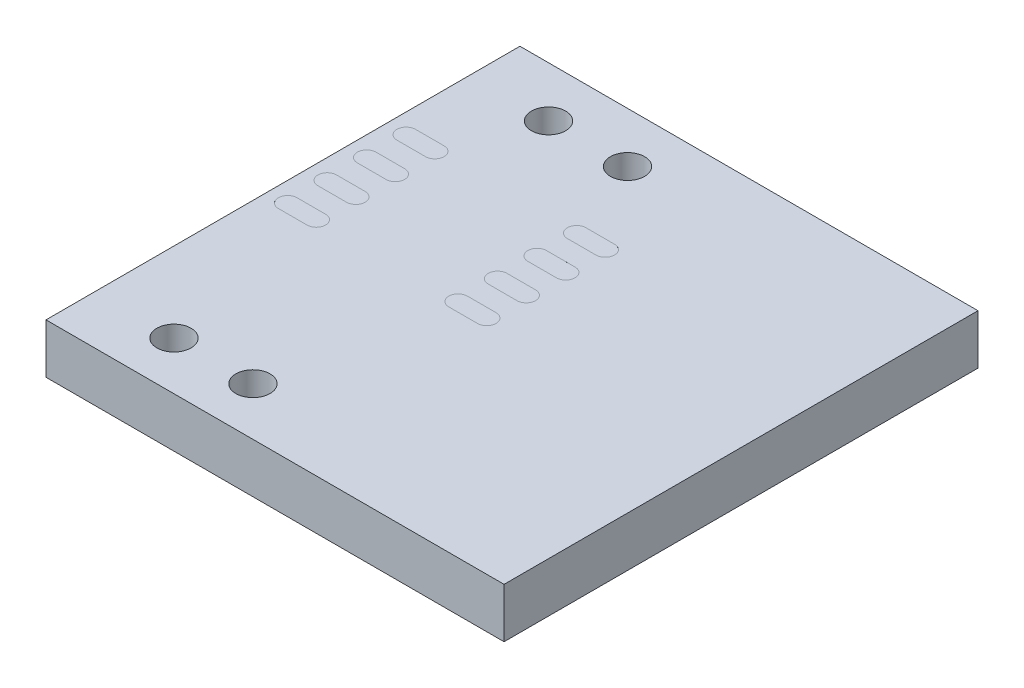
SolidWorks part; units mm, degrees
ref_plane "Front" through (0, 0, 0) normal (0, 0, 1) x (1, 0, 0)
ref_plane "Top" through (0, 0, 0) normal (0, 1, 0) x (1, 0, 0)
ref_plane "Right" through (0, 0, 0) normal (1, 0, 0) x (0, 0, -1)
sketch "Эскиз1" plane through (0, 0, 0) normal (0, 1, 0) x (1, 0, 0)
  line L1 (-7.365, 7.62) -> (7.365, 7.62)
  line L2 (-7.365, 7.62) -> (-7.365, -7.62)
  line L3 (-7.365, -7.62) -> (7.365, -7.62)
  line L4 (7.365, 7.62) -> (7.365, -7.62)
  line L5 (-7.365, 7.62) -> (7.365, -7.62) construction
  line L6 (-7.365, -7.62) -> (7.365, 7.62) construction
  point P0 (0, 0)
  dimension "D1" = 14.73
  dimension "D2" = 15.24
extrude "Бобышка-Вытянуть1" add sketch "Эскиз1" along normal blind 1.6
sketch "Эскиз2" plane through (0, 1.6, 0) normal (0, 1, 0) x (1, 0, 0)
  line L0 (-7.365, 7.62) -> (-7.365, -7.62) construction
  line L1 (7.365, 7.62) -> (-7.365, 7.62) construction
  line L2 (-7.365, -7.62) -> (7.365, -7.62) construction
  circle A0 centre (-4.825, 6) radius 0.55
  circle A1 centre (-2.285, 6) radius 0.55
  circle A2 centre (-4.8, -6.07) radius 0.55
  circle A3 centre (-2.26, -6.071) radius 0.55
  dimension "D5" = 1.1
  dimension "D6" = 1.1
  dimension "D11" = 1.1
  dimension "D12" = 1.1
  dimension "D1" = 2.54
  dimension "D2" = 2.54
  dimension "D3" = 1.62
  dimension "D4" = 1.62
  dimension "D7" = 2.565
  dimension "D8" = 2.54
  dimension "D9" = 1.549
  dimension "D10" = 1.55
extrude "Вырез-Вытянуть1" cut sketch "Эскиз2" against normal through all
sketch "Эскиз3" plane through (0, 1.6, 0) normal (0, 1, 0) x (1, 0, 0)
  line L0 (-6.729, 3.327) -> (-5.809, 3.327) construction
  line L1 (-6.729, 3.627) -> (-5.809, 3.627)
  line L2 (-6.729, 3.027) -> (-5.809, 3.027)
  line L3 (-7.365, 7.62) -> (-7.365, -7.62) construction
  line L4 (7.365, 7.62) -> (-7.365, 7.62) construction
  line L5 (-6.729, 2.057) -> (-5.809, 2.057) construction
  line L6 (-6.729, 2.357) -> (-5.809, 2.357)
  line L7 (-6.729, 1.757) -> (-5.809, 1.757)
  line L8 (-6.729, 0.787) -> (-5.809, 0.787) construction
  line L9 (-6.729, 1.087) -> (-5.809, 1.087)
  line L10 (-6.729, 0.487) -> (-5.809, 0.487)
  line L11 (-6.729, -0.483) -> (-5.809, -0.483) construction
  line L12 (-6.729, -0.183) -> (-5.809, -0.183)
  line L13 (-6.729, -0.783) -> (-5.809, -0.783)
  line L14 (-1.249, 2.057) -> (-0.329, 2.057) construction
  line L15 (-1.249, 2.357) -> (-0.329, 2.357)
  line L16 (-1.249, 1.757) -> (-0.329, 1.757)
  line L17 (-1.249, 0.787) -> (-0.329, 0.787) construction
  line L18 (-1.249, 1.087) -> (-0.329, 1.087)
  line L19 (-1.249, 0.487) -> (-0.329, 0.487)
  line L20 (-1.249, -0.483) -> (-0.329, -0.483) construction
  line L21 (-1.249, -0.183) -> (-0.329, -0.183)
  line L22 (-1.249, -0.783) -> (-0.329, -0.783)
  line L23 (-1.249, 3.327) -> (-0.329, 3.327) construction
  line L24 (-1.249, 3.627) -> (-0.329, 3.627)
  line L25 (-1.249, 3.027) -> (-0.329, 3.027)
  arc A0 (-6.729, 3.627) -> (-6.729, 3.027) centre (-6.729, 3.327) ccw
  arc A1 (-5.809, 3.027) -> (-5.809, 3.627) centre (-5.809, 3.327) ccw
  arc A2 (-6.729, 2.357) -> (-6.729, 1.757) centre (-6.729, 2.057) ccw
  arc A3 (-5.809, 1.757) -> (-5.809, 2.357) centre (-5.809, 2.057) ccw
  arc A4 (-6.729, 1.087) -> (-6.729, 0.487) centre (-6.729, 0.787) ccw
  arc A5 (-5.809, 0.487) -> (-5.809, 1.087) centre (-5.809, 0.787) ccw
  arc A6 (-6.729, -0.183) -> (-6.729, -0.783) centre (-6.729, -0.483) ccw
  arc A7 (-5.809, -0.783) -> (-5.809, -0.183) centre (-5.809, -0.483) ccw
  arc A8 (-1.249, 2.357) -> (-1.249, 1.757) centre (-1.249, 2.057) ccw
  arc A9 (-0.329, 1.757) -> (-0.329, 2.357) centre (-0.329, 2.057) ccw
  arc A10 (-1.249, 1.087) -> (-1.249, 0.487) centre (-1.249, 0.787) ccw
  arc A11 (-0.329, 0.487) -> (-0.329, 1.087) centre (-0.329, 0.787) ccw
  arc A12 (-1.249, -0.183) -> (-1.249, -0.783) centre (-1.249, -0.483) ccw
  arc A13 (-0.329, -0.783) -> (-0.329, -0.183) centre (-0.329, -0.483) ccw
  arc A14 (-1.249, 3.627) -> (-1.249, 3.027) centre (-1.249, 3.327) ccw
  arc A15 (-0.329, 3.027) -> (-0.329, 3.627) centre (-0.329, 3.327) ccw
  point P2 (-6.269, 3.327)
  point P16 (-6.269, 2.057)
  point P23 (-6.269, 0.787)
  point P30 (-6.269, -0.483)
  point P37 (-0.789, 2.057)
  point P44 (-0.789, 0.787)
  point P51 (-0.789, -0.483)
  point P58 (-0.789, 3.327)
  dimension "D1" = 0.6
  dimension "D2" = 0.92
  dimension "D3" = 1.096
  dimension "D4" = 4.293
  dimension "D5" = 4
  dimension "D6" = 2
extrude "Вырез-Вытянуть2" cut sketch "Эскиз3" against normal blind 0.0001
